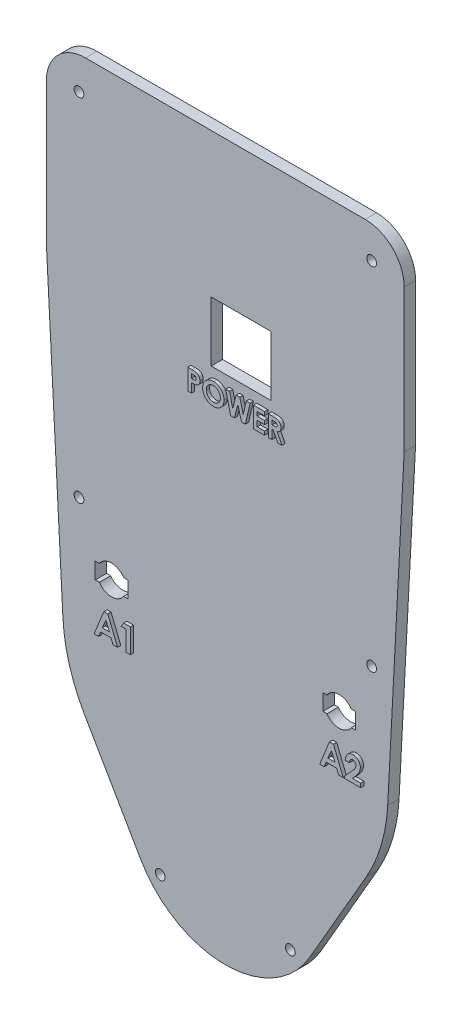
SolidWorks part; units mm, degrees
ref_plane "Front Plane" through (0, 0, 0) normal (0, 0, 1) x (1, 0, 0)
ref_plane "Top Plane" through (0, 0, 0) normal (0, 1, 0) x (1, 0, 0)
ref_plane "Right Plane" through (0, 0, 0) normal (1, 0, 0) x (0, 0, -1)
sketch "Sketch5" plane through (0, 0, 0) normal (0, 0, 1) x (1, 0, 0)
  line L0 (43.2975, -64.9823) -> (25.977, -94.9823)
  line L1 (-25.9845, -94.9823) -> (-43.305, -64.9823)
  line L2 (-49.9352, -42.599) -> (-55.0037, 54.1141)
  line L3 (-55.0037, 54.1141) -> (-55.0037, 98.0177)
  line L4 (-43.0037, 110.0177) -> (42.9963, 110.0177)
  line L5 (13.5591, 65.1953) -> (-3.8409, 65.1953)
  line L6 (-40, -22.5) -> (-40, -27.5)
  line L7 (-40, -27.5) -> (-38.7417, -27.5)
  line L8 (-31.2583, -27.5) -> (-30, -27.5)
  line L9 (-30, -27.5) -> (-30, -22.5)
  line L10 (-30, -22.5) -> (-31.2583, -22.5)
  line L11 (-38.7417, -22.5) -> (-40, -22.5)
  line L12 (54.9963, 98.0177) -> (54.9963, 54.1141)
  line L13 (31.2583, -22.5) -> (30, -22.5)
  line L14 (30, -22.5) -> (30, -27.5)
  line L15 (30, -27.5) -> (31.2583, -27.5)
  line L16 (38.7417, -27.5) -> (40, -27.5)
  line L17 (40, -27.5) -> (40, -22.5)
  line L18 (40, -22.5) -> (38.7417, -22.5)
  line L19 (13.5591, 47.7953) -> (13.5591, 65.1953)
  line L20 (-3.8409, 47.7953) -> (13.5591, 47.7953)
  line L21 (-3.8409, 65.1953) -> (-3.8409, 47.7953)
  line L22 (14.0591, 47.2953) -> (14.0591, 65.6953)
  line L23 (14.0591, 65.6953) -> (-4.3409, 65.6953)
  line L24 (-4.3409, 65.6953) -> (-4.3409, 47.2953)
  line L25 (-4.3409, 47.2953) -> (14.0591, 47.2953)
  line L26 (54.9963, 54.1141) -> (49.9277, -42.599)
  arc A0 (43.2975, -64.9823) -> (49.9277, -42.599) centre (-0.0037, -39.9823) ccw
  arc A1 (-25.9845, -94.9823) -> (25.977, -94.9823) centre (-0.0037, -79.9823) ccw
  arc A2 (-49.9352, -42.599) -> (-43.305, -64.9823) centre (-0.0037, -39.9823) ccw
  arc A3 (-43.0037, 110.0177) -> (-55.0037, 98.0177) centre (-43.0037, 98.0177) ccw
  arc A4 (54.9963, 98.0177) -> (42.9963, 110.0177) centre (42.9963, 98.0177) ccw
  circle A5 centre (-45, 100) radius 1.5
  circle A6 centre (45, 100) radius 1.5
  circle A7 centre (-45, -7.9998) radius 1.5
  circle A8 centre (45, -7.9998) radius 1.5
  arc A10 (-38.7417, -27.5) -> (-31.2583, -27.5) centre (-35, -25) ccw
  arc A11 (-31.2583, -22.5) -> (-38.7417, -22.5) centre (-35, -25) ccw
  arc A13 (38.7417, -22.5) -> (31.2583, -22.5) centre (35, -25) ccw
  arc A14 (31.2583, -27.5) -> (38.7417, -27.5) centre (35, -25) ccw
  circle A15 centre (-20, -96) radius 1.5
  circle A16 centre (20, -96) radius 1.5
extrude "Boss-Extrude2" add sketch "Sketch5" along normal blind 3.5 contours L12 A4 L4 A3 L3 L2 A2 L1 A1 L0 A0 L26 A16 A15 A14 L15 L14 L13 A13 L18 L17 L16 A11 L10 L9 L8 A10 L7 L6 L11 A8 A7 A6 A5 L25 L24 L23 L22
sketch "Sketch6" plane through (0, 0, 3.5) normal (0, 0, 1) x (1, 0, 0)
  text T0 "<b>POWER</b>" font "Century Gothic" height in points 24
  text T1 "<b>A1</b>" font "Century Gothic" height in points 28
  text T2 "<b>A2</b>" font "Century Gothic" height in points 28
  point P3 (-35.5275, -37.7908)
  point P4 (0, 0)
  point P5 (-38.5578, -39.6629)
  point P6 (-42.2154, -40.4907)
  point P7 (-37.3872, -40.42)
  point P8 (0, 0)
  point P9 (0, 0)
  point P10 (0, 0)
  point P11 (-39.4936, -41.0265)
  point P12 (0, 0)
  point P13 (29.9656, -39.2886)
  point P14 (0, 0)
  point P15 (29.8816, -41.0265)
  point P16 (-8.3442, 37.5307)
  point P17 (-11.7084, 38.1715)
  point P18 (0, 0)
  point P19 (0, 0)
  point P20 (-6.9502, 38.6936)
  point P21 (0, 0)
  point P22 (0, 0)
  point P23 (0, 0)
  point P24 (0, 0)
  point P25 (0, 0)
  point P26 (0, 0)
  point P27 (0, 0)
extrude "Boss-Extrude3" add sketch "Sketch6" along normal blind 1
